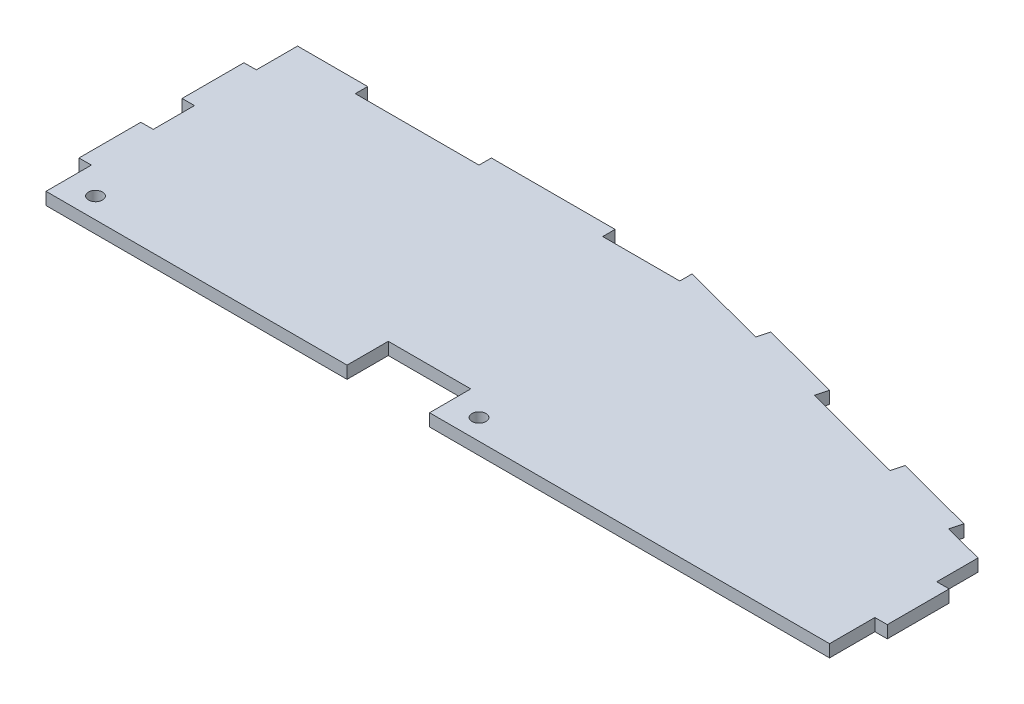
SolidWorks part; units mm, degrees
ref_plane "Front Plane" through (0, 0, 0) normal (0, 0, 1) x (1, 0, 0)
ref_plane "Top Plane" through (0, 0, 0) normal (0, 1, 0) x (1, 0, 0)
ref_plane "Right Plane" through (0, 0, 0) normal (1, 0, 0) x (0, 0, -1)
other "Configuration Table"
sketch "Sketch1" plane through (0, 0, 0) normal (0, 1, 0) x (1, 0, 0)
  line L1 (98, -30.5) -> (-98, -30.5)
  line L2 (98, -30.5) -> (98, 30.5)
  line L3 (98, 30.5) -> (-98, 30.5)
  line L4 (-98, -30.5) -> (-98, 30.5)
  line L5 (98, -30.5) -> (-98, 30.5) construction
  line L6 (98, 30.5) -> (-98, -30.5) construction
  point P0 (0, 0)
  dimension "D1" = 61
  dimension "D2" = 196
extrude "Boss-Extrude1" add sketch "Sketch1" along normal blind 3
sketch "Sketch2" plane through (0, 3, 0) normal (0, 1, 0) x (1, 0, 0)
  line L1 (-98, -30.5) -> (98, -30.5) construction
  line L5 (-95, 30.5) -> (-98, 30.5)
  line L6 (98, 30.5) -> (-98, 30.5) construction
  line L7 (-98, 30.5) -> (-98, 20.5)
  line L8 (-98, 30.5) -> (-98, -30.5) construction
  line L9 (-98, 20.5) -> (-95, 20.5)
  line L10 (-95, 20.5) -> (-95, 30.5)
  line L11 (-98, 5.5) -> (-95, 5.5)
  line L12 (-95, 5.5) -> (-95, -4.5)
  line L13 (-95, -4.5) -> (-98, -4.5)
  line L14 (-98, -4.5) -> (-98, 5.5)
  line L15 (-98, -19.5) -> (-95, -19.5)
  line L16 (-95, -19.5) -> (-95, -30.5)
  line L17 (-95, -30.5) -> (-98, -30.5)
  line L18 (-98, -30.5) -> (-98, -19.5)
  line L19 (98, 5.5) -> (98, -4.5)
  line L20 (98, -30.5) -> (98, 30.5) construction
  line L21 (98, -4.5) -> (95, -4.5)
  line L22 (95, -4.5) -> (95, 5.5)
  line L23 (95, 5.5) -> (98, 5.5)
  line L24 (98, -30.5) -> (98, -19.5)
  line L25 (98, -19.5) -> (95, -19.5)
  line L26 (95, -19.5) -> (95, -30.5)
  line L27 (95, -30.5) -> (98, -30.5)
  line L28 (42, 30.5) -> (42, 27.5)
  line L40 (-22, -30.5) -> (-22, -20.5)
  line L41 (-22, -20.5) -> (-2, -20.5)
  line L42 (-2, -20.5) -> (-2, -30.5)
  line L43 (-22, -30.5) -> (-2, -30.5)
  line L44 (-78, 30.5) -> (-78, 27.5)
  line L45 (-78, 27.5) -> (-48, 27.5)
  line L46 (-48, 27.5) -> (-48, 30.5)
  line L47 (-48, 30.5) -> (-78, 30.5)
  line L48 (42, 27.5) -> (72, 27.5)
  line L49 (72, 27.5) -> (72, 30.5)
  line L50 (72, 30.5) -> (42, 30.5)
  line L51 (-18, 30.5) -> (-18, 27.5)
  line L52 (-18, 27.5) -> (12, 27.5)
  line L53 (12, 27.5) -> (12, 30.5)
  line L54 (12, 30.5) -> (-18, 30.5)
  line L55 (98, 20.5) -> (95, 20.5)
  line L56 (95, 20.5) -> (95, 30.5)
  line L57 (95, 30.5) -> (98, 30.5)
  line L58 (98, 30.5) -> (98, 20.5)
  circle A0 centre (-88, -25.5) radius 1.7
  circle A1 centre (5, -25.5) radius 1.7
  dimension "D4" = 5
  dimension "D6" = 103
  dimension "D2" = 76
  dimension "D3" = 10
  dimension "D5" = 10
  dimension "D7" = 3
  dimension "D8" = 10
  dimension "D9" = 11
  dimension "D10" = 10
  dimension "D11" = 15
  dimension "D12" = 3
  dimension "D13" = 30
  dimension "D14" = 30
  dimension "D15" = 30
  dimension "D16" = 30
  dimension "D20" = 20
  dimension "D21" = 20
  dimension "D23" = 3
extrude "Cut-Extrude1" cut sketch "Sketch2" against normal blind 3
sketch "Sketch3" plane through (0, 3, 0) normal (0, 1, 0) x (1, 0, 0)
  line L0 (12, 30.5) -> (98, 30.5)
  line L1 (98, 30.5) -> (98, 5.5)
  line L2 (98, 5.5) -> (95, 5.5)
  line L3 (12, 30.5) -> (12, 27.5)
  line L4 (12, 27.5) -> (95, 5.5) construction
  line L5 (95, 5.5) -> (85.3338, 8.0621)
  line L6 (85.3338, 8.0621) -> (86.1024, 10.962)
  line L7 (86.1024, 10.962) -> (66.77, 16.0862)
  line L8 (66.77, 16.0862) -> (66.0014, 13.1864)
  line L9 (66.0014, 13.1864) -> (40.9986, 19.8136)
  line L10 (40.9986, 19.8136) -> (41.7673, 22.7135)
  line L11 (41.7673, 22.7135) -> (22.4348, 27.8377)
  line L12 (22.4348, 27.8377) -> (21.6662, 24.9379)
  line L13 (21.6662, 24.9379) -> (12, 27.5)
  point P14 (12, 27.5)
  dimension "D1" = 10
  dimension "D2" = 10
  dimension "D3" = 3
  dimension "D4" = 20
  dimension "D5" = 20
extrude "Cut-Extrude2" cut sketch "Sketch3" against normal blind 10
sketch "Sketch4" plane through (0, 3, 0) normal (0, 1, 0) x (1, 0, 0)
  line L0 (12, 27.5) -> (0.6818, 30.5)
  line L1 (12, 27.5) -> (21.6662, 24.9379) construction
  line L2 (0.6818, 30.5) -> (0.6818, 27.5)
  line L3 (-18, 27.5) -> (12, 27.5) construction
  line L4 (0.6818, 27.5) -> (12, 27.5)
extrude "Boss-Extrude2" add sketch "Sketch4" against normal blind 3
